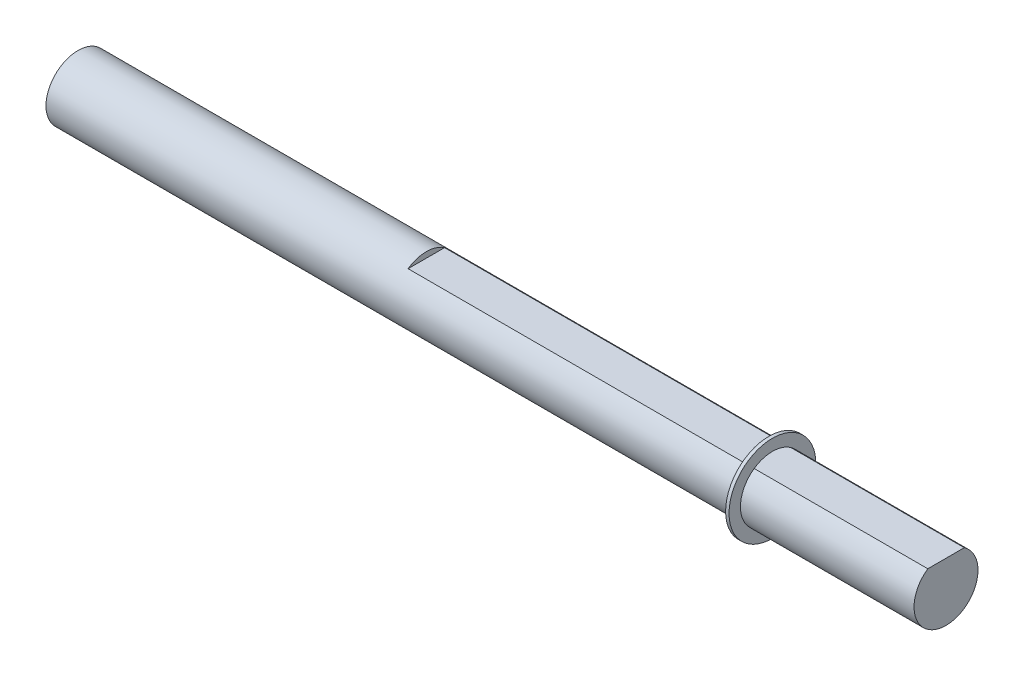
SolidWorks part; units mm, degrees
ref_plane "Plan de face" through (0, 0, 0) normal (0, 0, 1) x (1, 0, 0)
ref_plane "Plan de dessus" through (0, 0, 0) normal (0, 1, 0) x (1, 0, 0)
ref_plane "Plan de droite" through (0, 0, 0) normal (1, 0, 0) x (0, 0, -1)
sketch "Esquisse1" plane through (0, 0, 0) normal (0, 0, 1) x (1, 0, 0)
  line L0 (60.8, 2.8) -> (60.8, 3.8)
  line L1 (0, 0) -> (76, 0)
  line L2 (0, 0) -> (0, 2.8)
  line L3 (0, 2.8) -> (60.5, 2.8)
  line L4 (76, 0) -> (76, 2.8)
  line L5 (60.8, 3.8) -> (60.5, 3.8)
  line L6 (60.5, 3.8) -> (60.5, 2.8)
  line L7 (60.8, 2.8) -> (76, 2.8)
  dimension "D1" = 76
  dimension "D2" = 2.8
  dimension "D3" = 15.5
  dimension "D4" = 0.3
  dimension "D5" = 1
revolve "Révolution1" add sketch "Esquisse1" angle 360 about L1
sketch "Esquisse2" plane through (76, 0, 0) normal (1, 0, 0) x (0, 0, -1)
  line L0 (-1.5969, 2.3) -> (1.5969, 2.3)
  line L1 (-1.3775, -2.8) -> (1.8305, -2.8) construction
  circle A0 centre (0, 0) radius 2.8 construction
  arc A1 (1.5969, 2.3) -> (-1.5969, 2.3) centre (0, 0) ccw
  circle A2 centre (0, 0) radius 2.8 construction
  dimension "D1" = 5.1
extrude "Enlèv. mat.-Extru.1" cut sketch "Esquisse2" against normal offset from surface (45.5 mm away) 30.5 up to face at (0, 0, 2.8)
